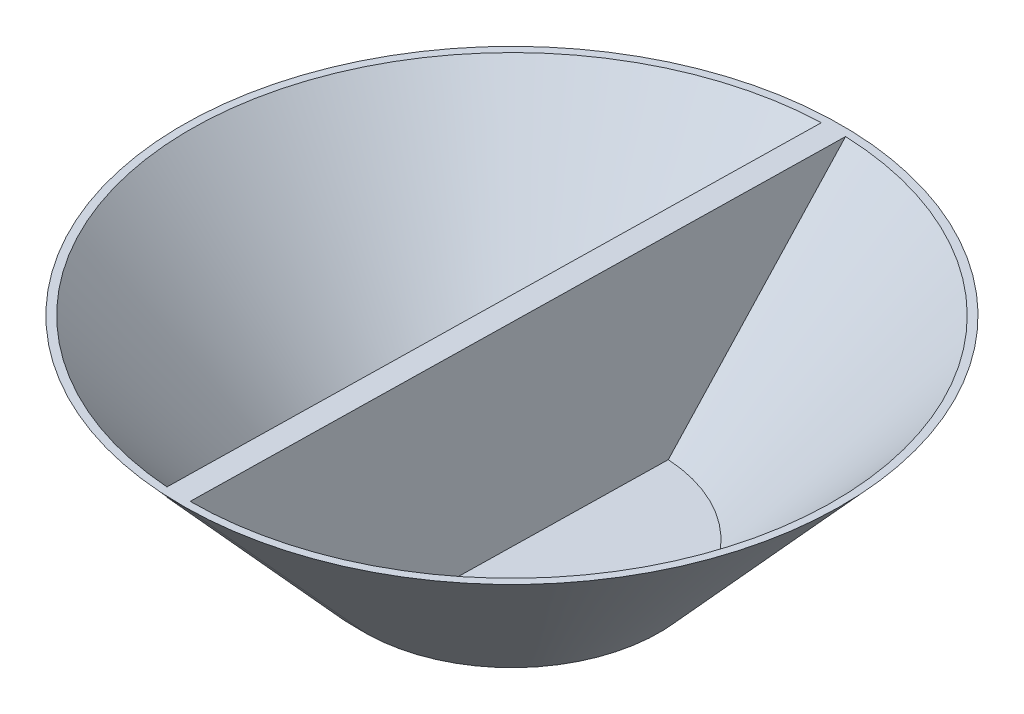
SolidWorks part; units mm, degrees
ref_plane "Front Plane" through (0, 0, 0) normal (0, 0, 1) x (1, 0, 0)
ref_plane "Top Plane" through (0, 0, 0) normal (0, 1, 0) x (1, 0, 0)
ref_plane "Right Plane" through (0, 0, 0) normal (1, 0, 0) x (0, 0, -1)
sketch "Sketch1" plane through (0, 0, 0) normal (0, 0, 1) x (1, 0, 0)
  line L0 (127, 271.5) -> (635, 271.5) construction
  line L1 (373.0985, 35.0697) -> (349.5985, 35.0697)
  line L2 (373.0985, 35.0697) -> (401.9756, 66.9398)
  line L3 (400.762, 66.9398) -> (401.9756, 66.9398)
  line L4 (349.5985, 66.9398) -> (349.5985, 35.0697) construction
  line L5 (349.5985, 36.0515) -> (373.0985, 36.0515)
  line L6 (373.0985, 36.0515) -> (400.762, 66.9398)
  line L7 (349.5985, 36.0515) -> (349.5985, 35.0697)
revolve "Revolve1" add sketch "Sketch1" angle 360 about L4
sketch "Sketch2" plane through (0, 66.9398, 0) normal (0, 1, 0) x (1, 0, 0)
  line L0 (347.683, 52.4121) -> (351.5141, 52.342)
  line L1 (347.683, 52.4121) -> (345.7687, -52.2369)
  line L2 (345.7687, -52.2369) -> (349.5985, -52.3771)
  line L3 (349.5985, -52.3771) -> (351.5141, 52.342)
  circle A0 centre (349.5985, 0) radius 52.3771
  point P6 (349.5985, 52.3771)
  circle M6 centre (349.5985, 0) radius 51.1634
extrude "Boss-Extrude1" add sketch "Sketch2" against normal blind 35 contours L3 L1 M6
sketch "Sketch3" plane through (350.4394, 0, 6.4103) normal (0.9998, 0, 0.0183) x (0.0183, 0, -0.9998)
  line L0 (-44.7606, 65.6003) -> (-17.0866, 35.0697)
  line L1 (-44.7606, 65.6003) -> (-44.7606, 31.9398)
  line L2 (-44.7606, 31.9398) -> (57.842, 31.9398)
  line L3 (57.842, 31.9398) -> (57.5483, 65.6003)
  line L4 (57.5483, 65.6003) -> (29.8743, 35.0697)
  line L5 (29.8743, 35.0697) -> (-17.0866, 35.0697)
extrude "Cut-Extrude2" cut sketch "Sketch3" against normal blind 10
ref_plane "Plane1" through (349.6207, 65.6003, 51.1634) normal (0, 1, 0) x (1, 0, 0)
ref_plane "Plane2" through (349.6207, 65.6003, 51.1634) normal (0, 1, 0) x (1, 0, 0)
sketch "Sketch6" plane through (0, 66.9398, 0) normal (0, 1, 0) x (1, 0, 0)
  line L0 (350.1095, -52.3746) -> (349.5985, -52.3771)
  line L1 (349.5985, -52.3771) -> (349.5985, -53.8877)
  line L2 (349.5985, -53.8877) -> (342.3792, -53.8877)
  line L3 (342.3792, -53.8877) -> (345.9889, -52.2526)
  line L4 (345.9889, -52.2526) -> (350.1095, -52.3746)
  circle A0 centre (349.5985, 0) radius 52.3771 construction
extrude "Cut-Extrude3" cut sketch "Sketch6" against normal blind 35
sketch "Sketch7" plane through (-0.8186, 0, 44.7531) normal (0.0183, 0, -0.9998) x (-0.9998, 0, -0.0183)
  line L0 (-348.5821, 31.9398) -> (-350.498, 31.9398)
  line L1 (-350.498, 31.9398) -> (-350.498, 65.6003)
  line L2 (-350.498, 31.9398) -> (-350.498, 65.6003) construction
  line L3 (-350.498, 65.6003) -> (-348.5821, 65.6003)
  line L4 (-348.5821, 65.6003) -> (-348.5821, 31.9398) construction
  line L5 (-348.5821, 65.6003) -> (-348.5821, 31.9398)
extrude "Cut-Extrude4" cut sketch "Sketch7" against normal blind 0.1 contours L5 L0 L1 L3
sketch "Sketch9" plane through (0, 66.9398, 0) normal (0, 1, 0) x (1, 0, 0)
  circle A2 centre (349.5985, 0) radius 52.3771
